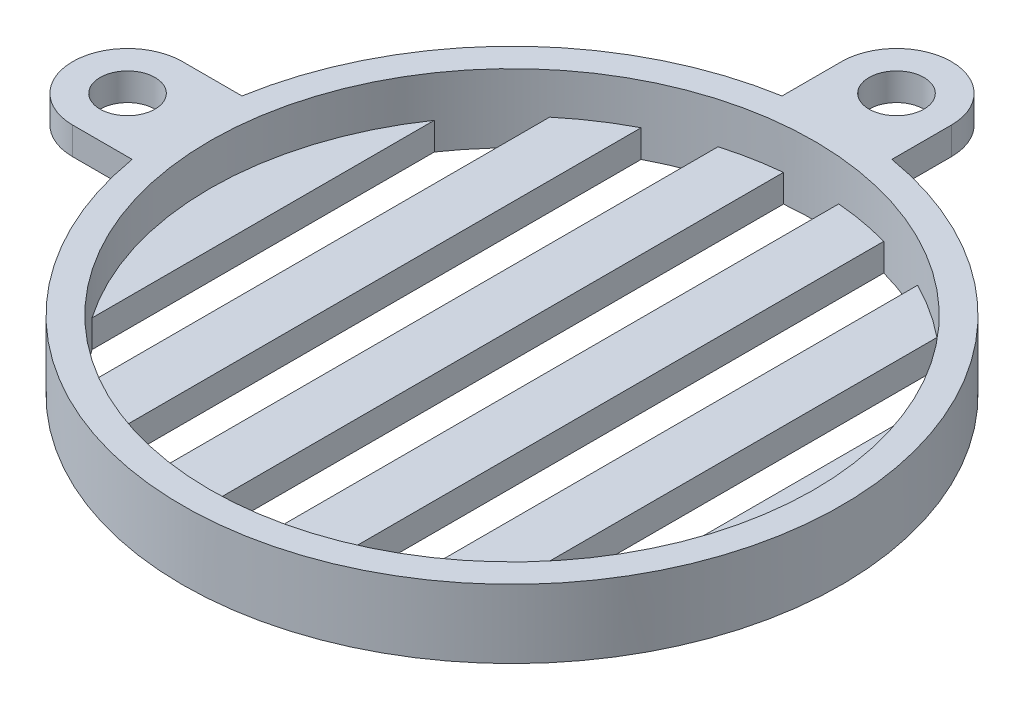
SolidWorks part; units mm, degrees
ref_plane "Front Plane" through (0, 0, 0) normal (0, 0, 1) x (1, 0, 0)
ref_plane "Top Plane" through (0, 0, 0) normal (0, 1, 0) x (1, 0, 0)
ref_plane "Right Plane" through (0, 0, 0) normal (1, 0, 0) x (0, 0, -1)
sketch "Sketch1" plane through (0, 0, 0) normal (0, 1, 0) x (1, 0, 0)
  circle A0 centre (0, 0) radius 22
  circle A1 centre (0, 0) radius 24
  dimension "D1" = 2
  dimension "D2" = 44
extrude "Boss-Extrude1" add sketch "Sketch1" along normal blind 5
sketch "Sketch2" plane through (0, 0, 0) normal (0, -1, 0) x (1, 0, 0)
  line L0 (-18.1268, 15.7295) -> (-18.1268, -15.7295)
  line L1 (-14.1268, -19.4019) -> (-14.1268, 19.4019)
  line L2 (-10.1268, 21.7588) -> (-10.1268, -21.7588)
  line L3 (-6.1268, 23.2048) -> (-6.1268, -23.2048)
  line L4 (-2.1268, 23.9056) -> (-2.1268, -23.9056)
  line L5 (1.8732, 23.9268) -> (1.8732, -23.9268)
  line L6 (5.8732, 23.2703) -> (5.8732, -23.2703)
  line L7 (9.8732, 21.8751) -> (9.8732, -21.8751)
  line L8 (13.8732, 19.5841) -> (13.8732, -19.5841)
  line L9 (17.8732, 16.0172) -> (17.8732, -16.0172)
  line L10 (21.8732, 9.8775) -> (21.8732, 3.8529)
  line L11 (21.8732, -3.8529) -> (21.8732, -9.8775)
  arc A1 (-14.1268, -19.4019) -> (-10.1268, -21.7588) centre (0, 0) ccw
  arc A2 (-18.1268, 15.7295) -> (-18.1268, -15.7295) centre (0, 0) ccw
  arc A3 (-10.1268, 21.7588) -> (-14.1268, 19.4019) centre (0, 0) ccw
  arc A4 (-6.1268, -23.2048) -> (-2.1268, -23.9056) centre (0, 0) ccw
  arc A5 (-2.1268, 23.9056) -> (-6.1268, 23.2048) centre (0, 0) ccw
  arc A6 (1.8732, -23.9268) -> (5.8732, -23.2703) centre (0, 0) ccw
  arc A7 (9.8732, -21.8751) -> (13.8732, -19.5841) centre (0, 0) ccw
  arc A8 (5.8732, 23.2703) -> (1.8732, 23.9268) centre (0, 0) ccw
  arc A9 (13.8732, 19.5841) -> (9.8732, 21.8751) centre (0, 0) ccw
  arc A10 (17.8732, -16.0172) -> (21.8732, -9.8775) centre (0, 0) ccw
  arc A11 (21.8732, 9.8775) -> (17.8732, 16.0172) centre (0, 0) ccw
  arc A12 (13.8732, 17.344) -> (9.8732, 19.8947) centre (0, 0) ccw
  arc A13 (21.8732, -3.8529) -> (21.8732, 3.8529) centre (0, 0) ccw
  arc A14 (-18.1268, 12.8335) -> (-18.1268, -12.8335) centre (0, 0) ccw
  arc A15 (-10.1268, 19.7668) -> (-14.1268, 17.1381) centre (0, 0) ccw
  arc A16 (-2.1268, 22.1078) -> (-6.1268, 21.3481) centre (0, 0) ccw
  arc A17 (5.8732, 21.4193) -> (1.8732, 22.1308) centre (0, 0) ccw
  arc A18 (-14.1268, -17.1381) -> (-10.1268, -19.7668) centre (0, 0) ccw
  arc A19 (-6.1268, -21.3481) -> (-2.1268, -22.1078) centre (0, 0) ccw
  arc A20 (1.8732, -22.1308) -> (5.8732, -21.4193) centre (0, 0) ccw
  arc A21 (9.8732, -19.8947) -> (13.8732, -17.344) centre (0, 0) ccw
  circle M13 centre (0, 0) radius 24
  circle M14 centre (0, 0) radius 22
  dimension "D1" = 4
  dimension "D2" = 4
  dimension "D3" = 4
  dimension "D4" = 4
  dimension "D5" = 4
  dimension "D6" = 4
  dimension "D7" = 4
  dimension "D8" = 4
  dimension "D9" = 4
  dimension "D10" = 4
extrude "Boss-Extrude2" add sketch "Sketch2" against normal blind 2 contours A14 L0 M13 | L0 M14 | L2 L1 M14 | L4 L3 M14 | L6 L5 M14 | L8 L7 M14 | L9 M14
sketch "Sketch3" plane through (0, 5, 0) normal (0, 1, 0) x (1, 0, 0)
  line L0 (-28, 4) -> (-22.8667, 4)
  line L1 (-22.8667, 4) -> (-22.8667, -4)
  line L2 (-22.8667, -4) -> (-28, -4)
  line L3 (-4, 22.8667) -> (-4, 28)
  line L4 (4, 22.8667) -> (-4, 22.8667)
  line L5 (4, 28) -> (4, 22.8667)
  circle A0 centre (0, 0) radius 28 construction
  circle A1 centre (-28, 0) radius 2
  arc A2 (-28, 4) -> (-28, -4) centre (-28, 0) ccw
  circle A3 centre (0, 0) radius 24 construction
  arc A4 (4, 28) -> (-4, 28) centre (0, 28) ccw
  circle A5 centre (0, 28) radius 2
  point P20 (0, 0)
  dimension "D1" = 4
  dimension "D2" = 2
  dimension "D3" = 2
extrude "Boss-Extrude3" add sketch "Sketch3" against normal blind 2
